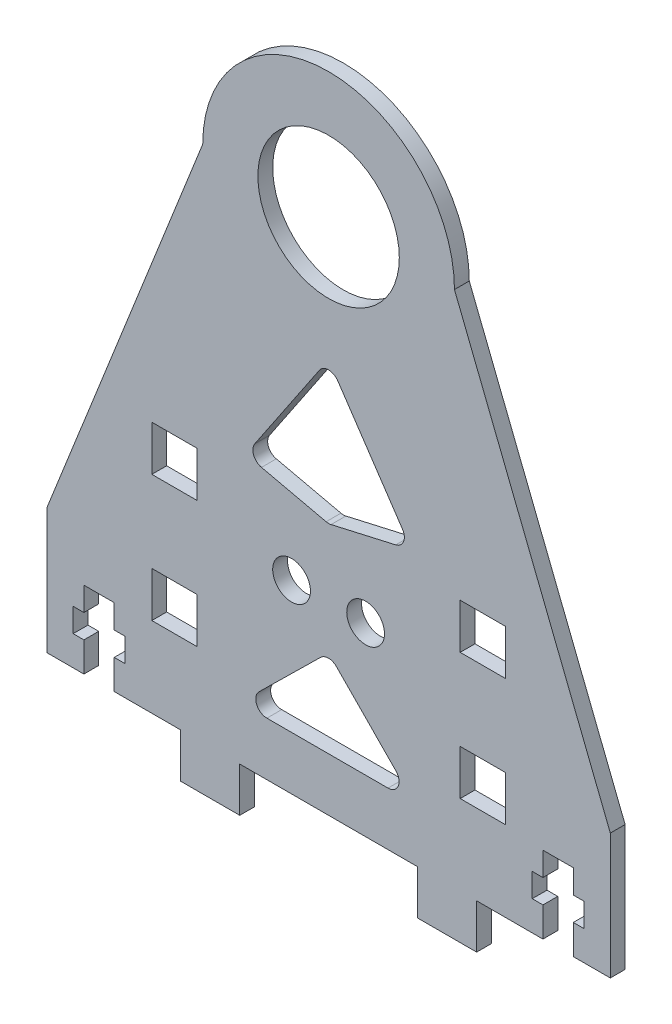
SolidWorks part; units mm, degrees
ref_plane "前视基准面" through (0, 0, 0) normal (0, 0, 1) x (1, 0, 0)
ref_plane "上视基准面" through (0, 0, 0) normal (0, 1, 0) x (1, 0, 0)
ref_plane "右视基准面" through (0, 0, 0) normal (1, 0, 0) x (0, 0, -1)
sketch "草图1" plane through (0, 0, 0) normal (0, 0, 1) x (1, 0, 0)
  line L0 (-30.7912, 3.1303) -> (31.2088, 3.1303) construction
  line L1 (-30.7912, 3.1303) -> (-30.7912, 5.1553) construction
  line L2 (-28.7412, 3.1303) -> (-28.7412, 7.1303)
  line L3 (-28.7412, 7.1303) -> (-27.2912, 7.1303)
  line L4 (-27.2912, 7.1303) -> (-27.2912, 10.3303)
  line L5 (-27.2912, 10.3303) -> (-28.7412, 10.3303)
  line L6 (-28.7412, 10.3303) -> (-28.7412, 13.5303)
  line L7 (-28.7412, 13.5303) -> (-32.8412, 13.5303)
  line L8 (-34.2912, 7.1303) -> (-34.2912, 10.3303)
  line L9 (-32.8412, 10.3303) -> (-32.8412, 13.5303)
  line L10 (-32.8412, 3.1303) -> (-32.8412, 7.1303)
  line L11 (-32.8412, 7.1303) -> (-34.2912, 7.1303)
  line L12 (-34.2912, 10.3303) -> (-32.8412, 10.3303)
  line L13 (-32.8412, 3.1303) -> (-37.8412, 3.1303)
  line L14 (-37.8412, 3.1303) -> (-37.8412, 90.1303) construction
  line L15 (-19.7912, 3.1303) -> (-19.7912, -2.8697)
  line L16 (-19.7912, -2.8697) -> (-11.7912, -2.8697)
  line L17 (-11.7912, -2.8697) -> (-11.7912, 3.1303)
  line L18 (-15.7912, -2.8697) -> (-15.7912, 3.1303) construction
  line L19 (-28.7412, 3.1303) -> (-19.7912, 3.1303)
  line L20 (0.2088, 3.1303) -> (0.2088, -7.8241) construction
  line L21 (-11.7912, 3.1303) -> (12.2088, 3.1303)
  line L22 (16.2088, -2.8697) -> (16.2088, 3.1303) construction
  line L23 (31.2088, 3.1303) -> (31.2088, 5.1553) construction
  line L24 (29.1588, 3.1303) -> (20.2088, 3.1303)
  line L25 (12.2088, -2.8697) -> (12.2088, 3.1303)
  line L26 (20.2088, -2.8697) -> (12.2088, -2.8697)
  line L27 (20.2088, 3.1303) -> (20.2088, -2.8697)
  line L28 (38.2588, 3.1303) -> (38.2588, 90.1303) construction
  line L29 (33.2588, 3.1303) -> (38.2588, 3.1303)
  line L30 (34.7088, 10.3303) -> (33.2588, 10.3303)
  line L31 (33.2588, 7.1303) -> (34.7088, 7.1303)
  line L32 (33.2588, 3.1303) -> (33.2588, 7.1303)
  line L33 (33.2588, 10.3303) -> (33.2588, 13.5303)
  line L34 (34.7088, 7.1303) -> (34.7088, 10.3303)
  line L35 (29.1588, 13.5303) -> (33.2588, 13.5303)
  line L36 (29.1588, 10.3303) -> (29.1588, 13.5303)
  line L37 (27.7088, 10.3303) -> (29.1588, 10.3303)
  line L38 (27.7088, 7.1303) -> (27.7088, 10.3303)
  line L39 (29.1588, 7.1303) -> (27.7088, 7.1303)
  line L40 (29.1588, 3.1303) -> (29.1588, 7.1303)
  line L41 (-37.8412, 90.1303) -> (38.2588, 90.1303) construction
  line L42 (0.2088, 3.1303) -> (0.2088, 73.1303) construction
  line L50 (-4.7912, 25.5803) -> (-34.2912, 25.5803) construction
  line L51 (-23.6625, 37.1803) -> (-17.5625, 37.1803)
  line L52 (-23.6625, 37.1803) -> (-23.6625, 31.0803)
  line L53 (-23.6625, 31.0803) -> (-17.5625, 31.0803)
  line L54 (-17.5625, 37.1803) -> (-17.5625, 31.0803)
  line L55 (-23.6625, 37.1803) -> (-17.5625, 31.0803) construction
  line L56 (-23.6625, 31.0803) -> (-17.5625, 37.1803) construction
  line L73 (-17.5625, 13.9803) -> (-17.5625, 20.0803)
  line L86 (-23.6625, 20.0803) -> (-17.5625, 20.0803)
  line L87 (-23.6625, 13.9803) -> (-23.6625, 20.0803)
  line L88 (-23.6625, 13.9803) -> (-17.5625, 13.9803)
  line L89 (-16.7912, 73.1303) -> (-37.8412, 20.0803)
  line L94 (0.2088, 22.1303) -> (-11.7912, 10.3303)
  line L95 (-11.7912, 10.3303) -> (11.8121, 10.3303)
  line L96 (11.8121, 10.3303) -> (0.2088, 22.1303)
  line L101 (-37.8412, 20.0803) -> (-37.8412, 3.1303)
  line L102 (24.0802, 31.0803) -> (17.9802, 31.0803)
  line L103 (17.9802, 37.1803) -> (17.9802, 31.0803)
  line L104 (24.0802, 37.1803) -> (24.0802, 31.0803)
  line L105 (24.0802, 37.1803) -> (17.9802, 37.1803)
  line L106 (24.0802, 20.0803) -> (17.9802, 20.0803)
  line L107 (24.0802, 13.9803) -> (24.0802, 20.0803)
  line L108 (17.9802, 13.9803) -> (17.9802, 20.0803)
  line L109 (24.0802, 13.9803) -> (17.9802, 13.9803)
  line L110 (38.2588, 20.0803) -> (38.2588, 3.1303)
  line L111 (17.2088, 73.1303) -> (38.2588, 20.0803)
  line L112 (-17.5625, 37.1803) -> (0.2088, 33.1303) construction
  line L113 (0.2088, 33.1303) -> (17.9802, 37.1803) construction
  line L114 (17.9802, 37.1803) -> (0.2088, 63.5803) construction
  line L115 (0.2088, 63.5803) -> (-17.5625, 37.1803) construction
  line L116 (0.2088, 56.4173) -> (-10.9877, 39.7845)
  line L117 (-10.9877, 39.7845) -> (0.2088, 37.2329)
  line L118 (0.2088, 37.2329) -> (11.4053, 39.7845)
  line L119 (11.4053, 39.7845) -> (0.2088, 56.4173)
  circle A0 centre (0.2088, 73.1303) radius 9.55
  circle A1 centre (0.2088, 73.1303) radius 40 construction
  circle A2 centre (-4.7912, 28.1303) radius 2.55
  circle A3 centre (5.2088, 28.1303) radius 2.55
  circle A6 centre (0.2088, 73.1303) radius 17 construction
  arc A8 (-16.7912, 73.1303) -> (17.2088, 73.1303) centre (0.2088, 73.1303) cw
  point P16 (-30.7912, 13.5303)
  point P47 (31.2088, 13.5303)
  point P55 (-20.6125, 34.1303)
  point P63 (-20.6125, 17.0303)
  dimension "D10" = 19.1
  dimension "D13" = 80
  dimension "D14" = 5.1
  dimension "D18" = 4
  dimension "D1" = 62
  dimension "D2" = 2.05
  dimension "D3" = 3.2
  dimension "D4" = 4
  dimension "D5" = 3.5
  dimension "D6" = 8
  dimension "D7" = 6
  dimension "D8" = 15
  dimension "D9" = 5
  dimension "D11" = 70
  dimension "D15" = 45
  dimension "D16" = 5
  dimension "D17" = 17.1
  dimension "D19" = 6.1
  dimension "D20" = 6.1
extrude "凸台-拉伸1" add sketch "草图1" along normal blind 2
sketch "草图2" plane through (0, 3.1303, 0) normal (0, -1, 0) x (1, 0, 0)
  line L0 (29.1588, 1) -> (33.2588, 1) construction
  line L1 (29.1588, 2) -> (29.1588, 0) construction
  line L2 (33.2588, 2) -> (33.2588, 0) construction
  circle A0 centre (31.2088, 1) radius 2.05
fillet "圆角3" radius 1.5 7 edges at (11.8121, 10.3303, 1) (-11.7912, 10.3303, 1) (0.2088, 22.1303, 1) (0.2088, 37.2329, 1) (11.4053, 39.7845, 1) (-10.9877, 39.7845, 1) (0.2088, 56.4173, 1)
